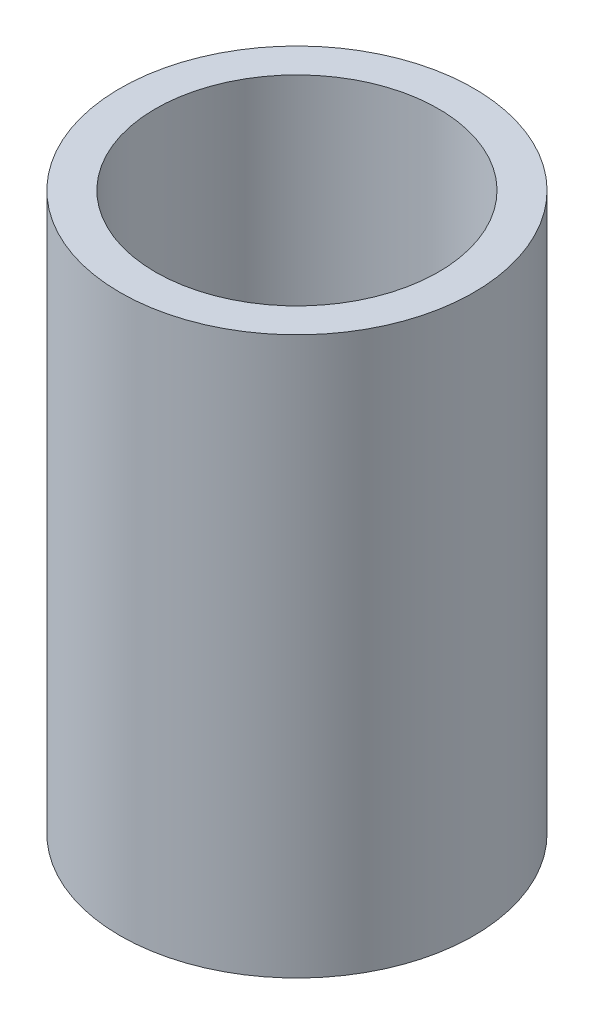
SolidWorks part; units mm, degrees
ref_plane "Front Plane" through (0, 0, 0) normal (0, 0, 1) x (1, 0, 0)
ref_plane "Top Plane" through (0, 0, 0) normal (0, 1, 0) x (1, 0, 0)
ref_plane "Right Plane" through (0, 0, 0) normal (1, 0, 0) x (0, 0, -1)
sketch "Sketch1" plane through (0, 0, 0) normal (0, 1, 0) x (1, 0, 0)
  circle A0 centre (0, 0) radius 12.7
  circle A1 centre (0, 0) radius 15.875
  point P5 (0, 0.302)
  dimension "D1" = 31.75
  dimension "D2" = 25.4
extrude "Boss-Extrude1" add sketch "Sketch1" along normal blind 50
